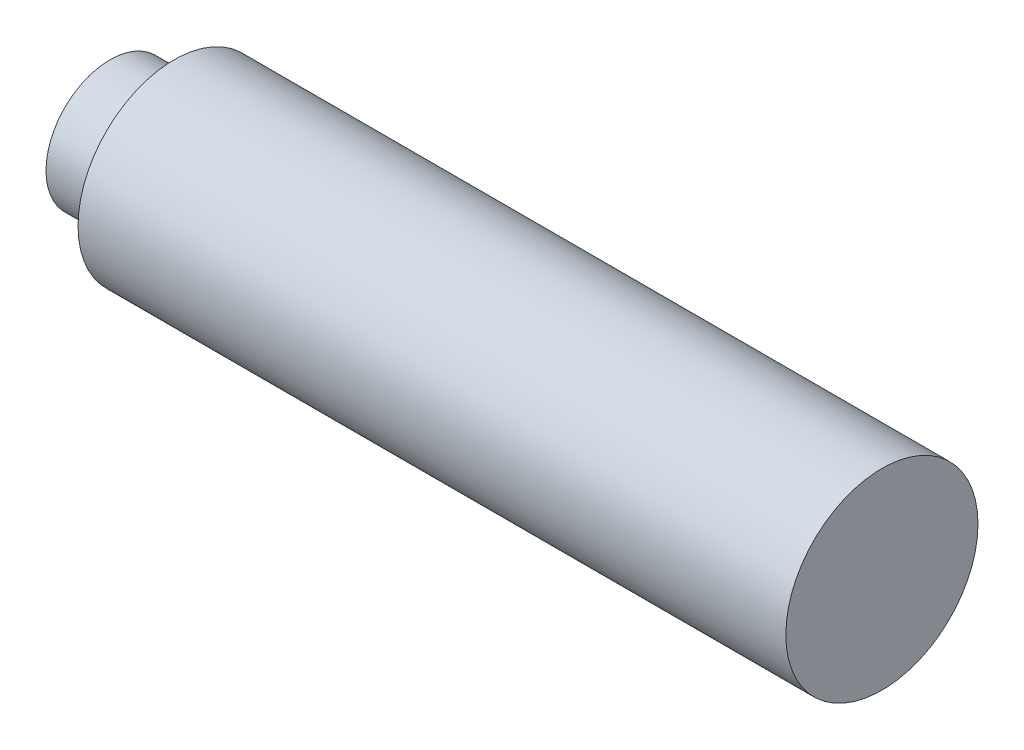
SolidWorks part; units mm, degrees
ref_plane "Plano frontal" through (0, 0, 0) normal (0, 0, 1) x (1, 0, 0)
ref_plane "Plano superior" through (0, 0, 0) normal (0, 1, 0) x (1, 0, 0)
ref_plane "Plano direito" through (0, 0, 0) normal (1, 0, 0) x (0, 0, -1)
sketch "Esboço1" plane through (0, 0, 0) normal (0, 0, 1) x (1, 0, 0)
  line L0 (-15.245, 0) -> (-15.245, 2.5)
  line L1 (-30.125, 2.5) -> (-30.125, 5)
  line L2 (30.125, 7.5) -> (30.125, 0)
  line L3 (-30.125, 5) -> (-25.125, 5)
  line L4 (-25.125, 5) -> (-25.125, 7.5)
  line L5 (-25.125, 7.5) -> (30.125, 7.5)
  line L6 (0, 0) -> (62.7162, 0) construction
  line L7 (30.125, 0) -> (-15.245, 0)
  line L8 (-15.245, 2.5) -> (-30.125, 2.5)
  point P4 (0, 0)
  dimension "D1" = 2.5
  dimension "D2" = 7.5
  dimension "D3" = 45.37
  dimension "D4" = 5
  dimension "D5" = 14.88
  dimension "D6" = 60.25
  dimension "D7" = 30.125
  dimension "D8" = 2.5
  dimension "D9" = 7.5
revolve "Revolução1" add sketch "Esboço1" angle 360 about L6
